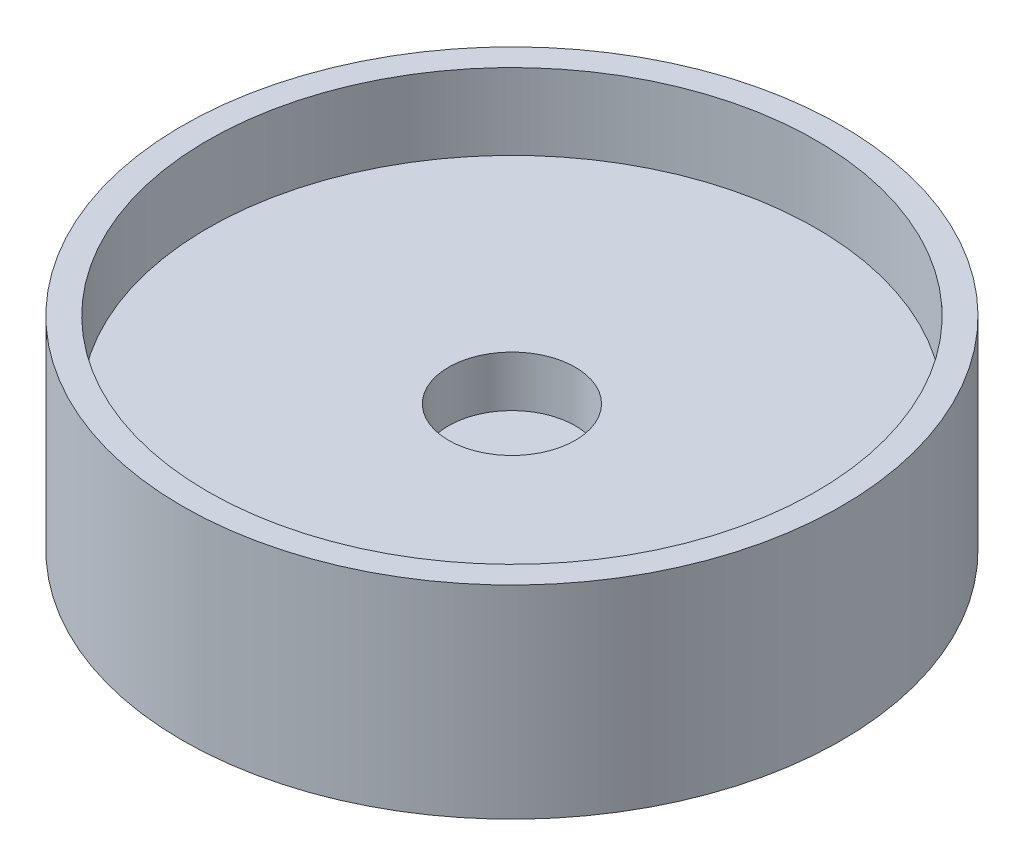
SolidWorks part; units mm, degrees
ref_plane "Front Plane" through (0, 0, 0) normal (0, 0, 1) x (1, 0, 0)
ref_plane "Top Plane" through (0, 0, 0) normal (0, 1, 0) x (1, 0, 0)
ref_plane "Right Plane" through (0, 0, 0) normal (1, 0, 0) x (0, 0, -1)
other "Configuration Table"
sketch "草图1" plane through (0, 0, 0) normal (0, 1, 0) x (1, 0, 0)
  circle A0 centre (0, 0) radius 13
  dimension "D1" = 26
extrude "凸台-拉伸1" add sketch "草图1" along normal blind 8
sketch "草图2" plane through (0, 8, 0) normal (0, 1, 0) x (1, 0, 0)
  circle A0 centre (0, 0) radius 12
  dimension "D1" = 24
extrude "切除-拉伸1" cut sketch "草图2" against normal blind 3
sketch "草图3" plane through (0, 5, 0) normal (0, 1, 0) x (1, 0, 0)
  circle A0 centre (0, 0) radius 2.5
  dimension "D1" = 5
extrude "切除-拉伸2" cut sketch "草图3" against normal blind 2
